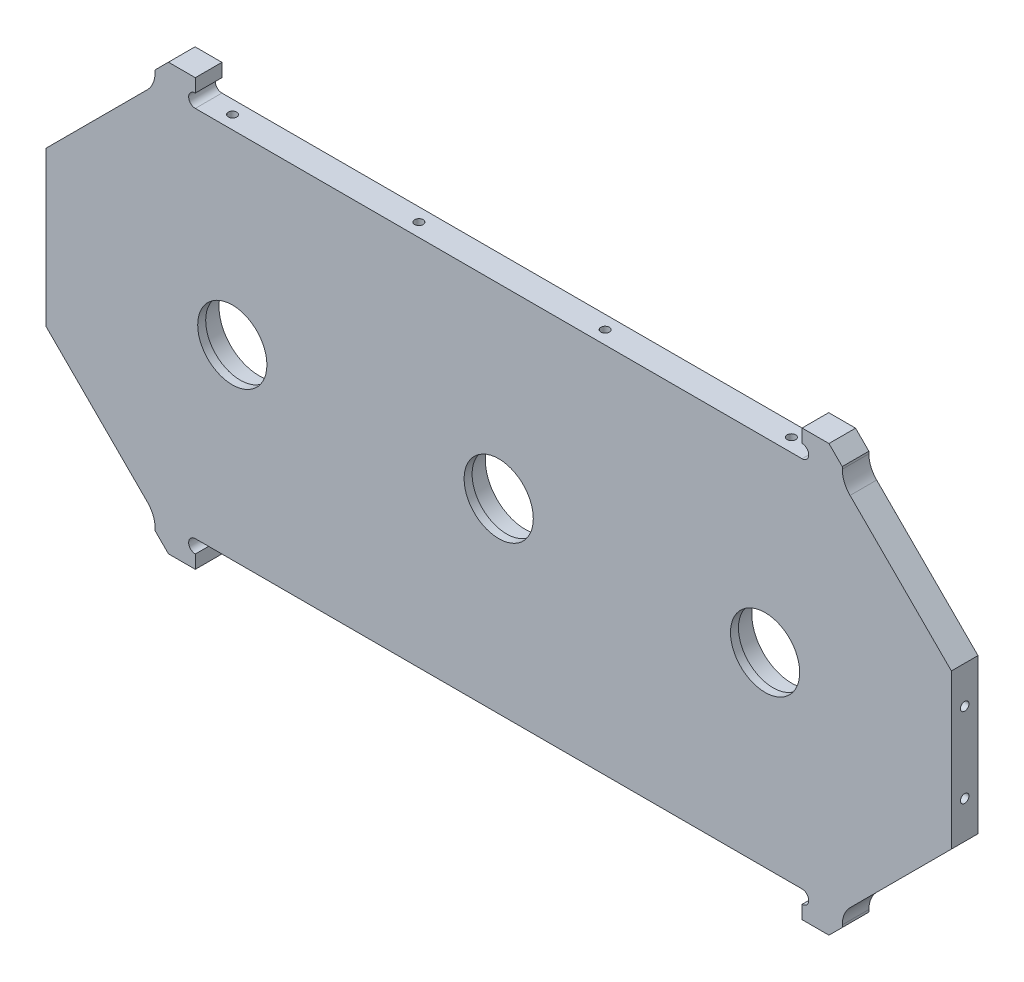
SolidWorks part; units mm, degrees
material "7075-T6，板材(SS)"
ref_plane "前视基准面" through (0, 0, 0) normal (0, 0, 1) x (1, 0, 0)
ref_plane "上视基准面" through (0, 0, 0) normal (0, 1, 0) x (1, 0, 0)
ref_plane "右视基准面" through (0, 0, 0) normal (1, 0, 0) x (0, 0, -1)
sketch "Sketch1" plane through (0, 0, 0) normal (0, 0, 1) x (1, 0, 0)
  line L0 (100.1, 0) -> (-100.1, 0) construction
  line L1 (100.1, -70) -> (-100.1, -70)
  line L2 (100.1, 70) -> (-100.1, 70)
  line L4 (-170.1, -28.9949) -> (-129.0949, -70)
  line L5 (-129.0949, -70) -> (-71.1051, -70)
  line L6 (-71.1051, -70) -> (-30.1, -28.9949)
  line L7 (-30.1, -28.9949) -> (-30.1, 28.9949)
  line L8 (-30.1, 28.9949) -> (-71.1051, 70)
  line L9 (-71.1051, 70) -> (-129.0949, 70)
  line L10 (-129.0949, 70) -> (-170.1, 28.9949)
  line L11 (-170.1, 28.9949) -> (-170.1, -28.9949)
  line L12 (129.0949, 70) -> (71.1051, 70)
  line L13 (71.1051, 70) -> (30.1, 28.9949)
  line L14 (30.1, 28.9949) -> (30.1, -28.9949)
  line L15 (30.1, -28.9949) -> (71.1051, -70)
  line L16 (71.1051, -70) -> (129.0949, -70)
  line L17 (129.0949, -70) -> (170.1, -28.9949)
  line L18 (170.1, -28.9949) -> (170.1, 28.9949)
  line L19 (170.1, 28.9949) -> (129.0949, 70)
  arc A0 (100.1, -70) -> (100.1, 70) centre (100.1, 0) ccw
  arc A1 (-100.1, 70) -> (-100.1, -70) centre (-100.1, 0) ccw
  circle A2 centre (-100.1, 0) radius 13
  circle A3 centre (0, 0) radius 13
  circle A4 centre (100.1, 0) radius 13
  circle A5 centre (-100.1, 0) radius 70 construction
  circle A6 centre (100.1, 0) radius 70 construction
  point P2 (0, 0)
  dimension "D1" = 70
  dimension "D3" = 26
  dimension "D2" = 200.2
extrude "Extrude1" add sketch "Sketch1" along normal blind 10 contours A1 L9 L10 | A1 L10 L11 | A1 L11 L4 | A1 L4 L5 | L2 A1 L1 L6 L7 L8 A2 | L15 L14 L13 L2 L8 L7 L6 L1 A3 | A0 L2 L13 L14 L15 L1 A4 | A0 L16 L17 | A0 L17 L18 | A0 L18 L19 | A0 L19 L12
sketch "Sketch2" plane through (0, 0, 0) normal (0, 0, -1) x (-1, 0, 0)
  circle A0 centre (0, 0) radius 15
  circle A1 centre (-100.1, 0) radius 15
  circle A2 centre (100.1, 0) radius 15
  dimension "D1" = 30
extrude "Extrude2" cut sketch "Sketch2" against normal blind 7
sketch "Sketch3" plane through (0, 0, 0) normal (0, 0, -1) x (-1, 0, 0)
  line L0 (126.6097, 64) -> (-126.6097, 64)
  line L1 (-126.6097, 64) -> (-164.1, 26.5097)
  line L2 (-164.1, 26.5097) -> (-164.1, -26.5097)
  line L3 (-164.1, -26.5097) -> (-126.6097, -64)
  line L4 (-126.6097, -64) -> (126.6097, -64)
  line L5 (126.6097, -64) -> (164.1, -26.5097)
  line L6 (164.1, -26.5097) -> (164.1, 26.5097)
  line L7 (164.1, 26.5097) -> (126.6097, 64)
  line L8 (-129.0949, -70) -> (129.0949, -70)
  line L9 (129.0949, -70) -> (170.1, -28.9949)
  line L10 (170.1, -28.9949) -> (170.1, 28.9949)
  line L11 (170.1, 28.9949) -> (129.0949, 70)
  line L12 (129.0949, 70) -> (-129.0949, 70)
  line L13 (-129.0949, 70) -> (-170.1, 28.9949)
  line L14 (-170.1, 28.9949) -> (-170.1, -28.9949)
  line L15 (-170.1, -28.9949) -> (-129.0949, -70)
  line L16 (-129.0949, -70) -> (129.0949, -70)
  line L17 (129.0949, -70) -> (170.1, -28.9949)
  line L18 (170.1, -28.9949) -> (170.1, 28.9949)
  line L19 (170.1, 28.9949) -> (129.0949, 70)
  line L20 (129.0949, 70) -> (-129.0949, 70)
  line L21 (-129.0949, 70) -> (-170.1, 28.9949)
  line L22 (-170.1, 28.9949) -> (-170.1, -28.9949)
  line L23 (-170.1, -28.9949) -> (-129.0949, -70)
  line L24 (-100.1, 0) -> (-168.983, 166.2983) construction
  line L25 (-101.9478, -0.7654) -> (-170.8308, 165.5329)
  line L26 (-98.2522, 0.7654) -> (-167.1353, 167.0637)
  line L27 (-100.1, 0) -> (-31.217, 166.2983) construction
  line L28 (-101.9478, 0.7654) -> (-33.0647, 167.0637)
  line L29 (-98.2522, -0.7654) -> (-29.3692, 165.5329)
  line L30 (-100.1, 0) -> (66.1983, 68.883) construction
  line L31 (-100.8654, 1.8478) -> (65.4329, 70.7308)
  line L32 (-99.3346, -1.8478) -> (66.9637, 67.0353)
  line L33 (-100.1, 0) -> (66.1983, -68.883) construction
  line L34 (-99.3346, 1.8478) -> (66.9637, -67.0353)
  line L35 (-100.8654, -1.8478) -> (65.4329, -70.7308)
  line L36 (-100.1, 0) -> (-31.217, -166.2983) construction
  line L37 (-98.2522, 0.7654) -> (-29.3692, -165.5329)
  line L38 (-101.9478, -0.7654) -> (-33.0647, -167.0637)
  line L39 (-100.1, 0) -> (-168.983, -166.2983) construction
  line L40 (-98.2522, -0.7654) -> (-167.1353, -167.0637)
  line L41 (-101.9478, 0.7654) -> (-170.8308, -165.5329)
  line L42 (-100.1, 0) -> (-266.3983, -68.883) construction
  line L43 (-99.3346, -1.8478) -> (-265.6329, -70.7308)
  line L44 (-100.8654, 1.8478) -> (-267.1637, -67.0353)
  line L45 (-100.1, 0) -> (-266.3983, 68.883) construction
  line L46 (-100.8654, -1.8478) -> (-267.1637, 67.0353)
  line L47 (-99.3346, 1.8478) -> (-265.6329, 70.7308)
  line L48 (0, 0) -> (0, -70) construction
  line L49 (100.1, 0) -> (168.983, 166.2983) construction
  line L50 (101.9478, -0.7654) -> (170.8308, 165.5329)
  line L51 (98.2522, 0.7654) -> (167.1353, 167.0637)
  line L52 (100.1, 0) -> (31.217, 166.2983) construction
  line L53 (101.9478, 0.7654) -> (33.0647, 167.0637)
  line L54 (98.2522, -0.7654) -> (29.3692, 165.5329)
  line L55 (100.1, 0) -> (-66.1983, 68.883) construction
  line L56 (100.8654, 1.8478) -> (-65.4329, 70.7308)
  line L57 (99.3346, -1.8478) -> (-66.9637, 67.0353)
  line L58 (100.1, 0) -> (-66.1983, -68.883) construction
  line L59 (99.3346, 1.8478) -> (-66.9637, -67.0353)
  line L60 (100.8654, -1.8478) -> (-65.4329, -70.7308)
  line L61 (100.1, 0) -> (31.217, -166.2983) construction
  line L62 (98.2522, 0.7654) -> (29.3692, -165.5329)
  line L63 (101.9478, -0.7654) -> (33.0647, -167.0637)
  line L64 (100.1, 0) -> (168.983, -166.2983) construction
  line L65 (98.2522, -0.7654) -> (167.1353, -167.0637)
  line L66 (101.9478, 0.7654) -> (170.8308, -165.5329)
  line L67 (100.1, 0) -> (266.3983, -68.883) construction
  line L68 (99.3346, -1.8478) -> (265.6329, -70.7308)
  line L69 (100.8654, 1.8478) -> (267.1637, -67.0353)
  line L70 (100.1, 0) -> (266.3983, 68.883) construction
  line L71 (100.8654, -1.8478) -> (267.1637, 67.0353)
  line L72 (99.3346, 1.8478) -> (265.6329, 70.7308)
  line L73 (170.1, -28.9949) -> (129.0949, -70)
  line L74 (170.1, 28.9949) -> (170.1, -28.9949)
  line L75 (129.0949, 70) -> (170.1, 28.9949)
  line L76 (-129.0949, 70) -> (129.0949, 70)
  line L77 (-170.1, 28.9949) -> (-129.0949, 70)
  line L78 (-170.1, -28.9949) -> (-170.1, 28.9949)
  line L79 (-129.0949, -70) -> (-170.1, -28.9949)
  line L80 (129.0949, -70) -> (-129.0949, -70)
  line L81 (-164.1, 26.5097) -> (-126.6097, 64)
  line L82 (-164.1, -26.5097) -> (-164.1, 26.5097)
  line L83 (-126.6097, -64) -> (-164.1, -26.5097)
  line L84 (126.6097, -64) -> (-126.6097, -64)
  line L85 (164.1, -26.5097) -> (126.6097, -64)
  line L86 (164.1, 26.5097) -> (164.1, -26.5097)
  line L87 (126.6097, 64) -> (164.1, 26.5097)
  line L88 (-126.6097, 64) -> (126.6097, 64)
  line L89 (0, 70) -> (0, -70) construction
  line L90 (2, 70) -> (2, -70)
  line L91 (-2, 70) -> (-2, -70)
  line L92 (-100.1, 0) -> (100.1, 0) construction
  line L93 (-100.1, 2) -> (100.1, 2)
  line L94 (-100.1, -2) -> (100.1, -2)
  arc A0 (-101.9478, -0.7654) -> (-98.2522, 0.7654) centre (-100.1, 0) ccw
  arc A1 (-167.1353, 167.0637) -> (-170.8308, 165.5329) centre (-168.983, 166.2983) ccw
  arc A2 (-101.9478, 0.7654) -> (-98.2522, -0.7654) centre (-100.1, 0) ccw
  arc A3 (-29.3692, 165.5329) -> (-33.0647, 167.0637) centre (-31.217, 166.2983) ccw
  arc A4 (-100.8654, 1.8478) -> (-99.3346, -1.8478) centre (-100.1, 0) ccw
  arc A5 (66.9637, 67.0353) -> (65.4329, 70.7308) centre (66.1983, 68.883) ccw
  arc A6 (-99.3346, 1.8478) -> (-100.8654, -1.8478) centre (-100.1, 0) ccw
  arc A7 (65.4329, -70.7308) -> (66.9637, -67.0353) centre (66.1983, -68.883) ccw
  arc A8 (-98.2522, 0.7654) -> (-101.9478, -0.7654) centre (-100.1, 0) ccw
  arc A9 (-33.0647, -167.0637) -> (-29.3692, -165.5329) centre (-31.217, -166.2983) ccw
  arc A10 (-98.2522, -0.7654) -> (-101.9478, 0.7654) centre (-100.1, 0) ccw
  arc A11 (-170.8308, -165.5329) -> (-167.1353, -167.0637) centre (-168.983, -166.2983) ccw
  arc A12 (-99.3346, -1.8478) -> (-100.8654, 1.8478) centre (-100.1, 0) ccw
  arc A13 (-267.1637, -67.0353) -> (-265.6329, -70.7308) centre (-266.3983, -68.883) ccw
  arc A14 (-100.8654, -1.8478) -> (-99.3346, 1.8478) centre (-100.1, 0) ccw
  arc A15 (-265.6329, 70.7308) -> (-267.1637, 67.0353) centre (-266.3983, 68.883) ccw
  arc A16 (101.9478, -0.7654) -> (98.2522, 0.7654) centre (100.1, 0) cw
  arc A17 (167.1353, 167.0637) -> (170.8308, 165.5329) centre (168.983, 166.2983) cw
  arc A18 (101.9478, 0.7654) -> (98.2522, -0.7654) centre (100.1, 0) cw
  arc A19 (29.3692, 165.5329) -> (33.0647, 167.0637) centre (31.217, 166.2983) cw
  arc A20 (100.8654, 1.8478) -> (99.3346, -1.8478) centre (100.1, 0) cw
  arc A21 (-66.9637, 67.0353) -> (-65.4329, 70.7308) centre (-66.1983, 68.883) cw
  arc A22 (99.3346, 1.8478) -> (100.8654, -1.8478) centre (100.1, 0) cw
  arc A23 (-65.4329, -70.7308) -> (-66.9637, -67.0353) centre (-66.1983, -68.883) cw
  arc A24 (98.2522, 0.7654) -> (101.9478, -0.7654) centre (100.1, 0) cw
  arc A25 (33.0647, -167.0637) -> (29.3692, -165.5329) centre (31.217, -166.2983) cw
  arc A26 (98.2522, -0.7654) -> (101.9478, 0.7654) centre (100.1, 0) cw
  arc A27 (170.8308, -165.5329) -> (167.1353, -167.0637) centre (168.983, -166.2983) cw
  arc A28 (99.3346, -1.8478) -> (100.8654, 1.8478) centre (100.1, 0) cw
  arc A29 (267.1637, -67.0353) -> (265.6329, -70.7308) centre (266.3983, -68.883) cw
  arc A30 (100.8654, -1.8478) -> (99.3346, 1.8478) centre (100.1, 0) cw
  arc A31 (265.6329, 70.7308) -> (267.1637, 67.0353) centre (266.3983, 68.883) cw
  circle A34 centre (-100.1, 0) radius 19
  circle A35 centre (-100.1, 0) radius 19
  circle A37 centre (0, 0) radius 19
  circle A38 centre (0, 0) radius 19
  arc A39 (2, 70) -> (-2, 70) centre (0, 70) ccw
  circle A40 centre (100.1, 0) radius 19
  circle A41 centre (100.1, 0) radius 19
  arc A42 (-2, -70) -> (2, -70) centre (0, -70) ccw
  arc A43 (-100.1, 2) -> (-100.1, -2) centre (-100.1, 0) ccw
  arc A44 (100.1, -2) -> (100.1, 2) centre (100.1, 0) ccw
  point P19 (-134.5415, 83.1492)
  point P28 (-65.6585, 83.1492)
  point P35 (-16.9508, 34.4415)
  point P42 (-16.9508, -34.4415)
  point P49 (-65.6585, -83.1492)
  point P56 (-134.5415, -83.1492)
  point P63 (-183.2492, -34.4415)
  point P70 (-183.2492, 34.4415)
  point P78 (134.5415, 83.1492)
  point P85 (65.6585, 83.1492)
  point P92 (16.9508, 34.4415)
  point P99 (16.9508, -34.4415)
  point P106 (65.6585, -83.1492)
  point P113 (134.5415, -83.1492)
  point P120 (183.2492, -34.4415)
  point P127 (183.2492, 34.4415)
  point P133 (0, 0)
  point P148 (0, 0)
  dimension "D3" = 4
  dimension "D5" = 180
  dimension "D9" = 4
  dimension "D10" = 4
  dimension "D1" = 0
  dimension "D2" = 6
  dimension "D6" = 4
  dimension "D7" = 4
  dimension "D8" = 4
  dimension "D4" = 8
extrude "Extrude3" cut sketch "Sketch3" against normal blind 8 contours A35 L25 L1 L47 | A35 L46 L2 L44 | A35 L43 L3 L41 | A35 L40 L4 L38 | A35 L37 L4 L59 L35 | A38 L94 A35 L34 L91 | A38 L91 L32 A35 L93 | A35 L31 L57 L0 L29 | A35 L28 L0 L26 | L91 L0 L56 | L88 L91 L56 L31 L90 | L0 L90 L31 | L91 L60 L4 | L35 L90 L84 | L60 L91 L84 L90 L35 | A41 L60 L34 L4 L62 | A41 L94 A38 L90 L59 | A41 L57 L90 A38 L93 | A41 L54 L0 L32 L56 | A41 L51 L0 L53 | A41 L72 L7 L50 | A41 L69 L6 L71 | A41 L66 L5 L68 | A41 L63 L4 L65
fillet "Fillet2" radius 2 86 edges at (-83.4092, -9.0783, 4) (-5.2263, -41.4628, 4) (-59.6359, -64, 4) (-71.4255, -64, 4) (-91.0217, -16.6908, 4) (0, 43.6276, 4) (-49.1834, 64, 4) (49.1834, 64, 4) (-116.7908, 9.0783, 4) (-162.5693, 28.0404, 4) (-128.1404, 62.4693, 4) (-109.1783, 16.6908, 4) (-91.0217, 16.6908, 4) (-71.4255, 64, 4) (-59.6359, 64, 4) (-5.2263, 41.4628, 4) (-83.4092, 9.0783, 4) (91.0217, -16.6908, 4) (71.4255, -64, 4) (59.6359, -64, 4) (5.2263, -41.4628, 4) (83.4092, -9.0783, 4) (116.7908, -9.0783, 4) (162.5693, -28.0404, 4) (128.1404, -62.4693, 4) (109.1783, -16.6908, 4) (94.7172, 18.2216, 4) (75.7551, 64, 4) (124.4449, 64, 4) (105.4828, 18.2216, 4) (18.8944, -2, 4) (81.2056, -2, 4) (81.8784, -5.3828, 4) (2, -38.4696, 4) (2, -18.8944, 4) (-118.3216, -5.3828, 4) (-164.1, -24.3449, 4) (-164.1, 24.3449, 4) (-118.3216, 5.3828, 4) (109.1783, 16.6908, 4) (128.1404, 62.4693, 4) (162.5693, 28.0404, 4) (116.7908, 9.0783, 4) (-109.1783, -16.6908, 4) (-128.1404, -62.4693, 4) (-162.5693, -28.0404, 4) (-116.7908, -9.0783, 4) (-94.7172, -18.2216, 4) (-75.7551, -64, 4) (-124.4449, -64, 4) (-105.4828, -18.2216, 4) (2, 18.8944, 4) (2, 38.4696, 4) (81.8784, 5.3828, 4) (81.2056, 2, 4) (83.4092, 9.0783, 4) (5.2263, 41.4628, 4) (59.6359, 64, 4) (71.4255, 64, 4) (91.0217, 16.6908, 4) (118.3216, 5.3828, 4) (164.1, 24.3449, 4) (164.1, -24.3449, 4) (118.3216, -5.3828, 4) (105.4828, -18.2216, 4) (124.4449, -64, 4) (75.7551, -64, 4) (94.7172, -18.2216, 4) (-81.8784, 5.3828, 4) (-2, 38.4696, 4) (-2, 18.8944, 4) (-18.8944, 2, 4) (-81.2056, 2, 4) (-105.4828, 18.2216, 4) (-124.4449, 64, 4) (-75.7551, 64, 4) (-94.7172, 18.2216, 4) (0, -43.6276, 4) (49.1834, -64, 4) (-49.1834, -64, 4) (-81.2056, -2, 4) (-18.8944, -2, 4) (-2, -18.8944, 4) (-2, -38.4696, 4) (-81.8784, -5.3828, 4) (18.8944, 2, 4)
sketch "Sketch4" plane through (0, 70, 0) normal (0, 1, 0) x (1, 0, 0)
  line L0 (0, 0) -> (0, -10) construction
  line L1 (129.0949, -10) -> (-129.0949, -10) construction
  line L2 (105, -5) -> (35, -5) construction
  line L3 (35, -5) -> (-35, -5) construction
  circle A0 centre (35, -5) radius 1.6
  circle A1 centre (105, -5) radius 1.6
  circle A2 centre (-105, -5) radius 1.6
  circle A3 centre (-35, -5) radius 1.6
  point P7 (0, -5)
  dimension "D1" = 3.2
  dimension "D2" = 70
extrude "Extrude4" cut sketch "Sketch4" against normal blind 6
cosmetic thread "Cosmetic Thread1" parameters "D2"=4
cosmetic thread "Cosmetic Thread2" parameters "D2"=4
cosmetic thread "Cosmetic Thread3" parameters "D2"=4
cosmetic thread "Cosmetic Thread4" parameters "D2"=4
sketch "Sketch5" plane through (0, 0, 0) normal (0, 0, -1) x (-1, 0, 0)
  line L0 (0, 70) -> (0, 0) construction
  line L1 (-129.0949, 70) -> (-114, 70)
  line L2 (-129.0949, 70) -> (-129.0949, 80)
  line L3 (-129.0949, 80) -> (-114, 80)
  line L4 (-114, 70) -> (-114, 80)
  line L5 (-129.0949, 70) -> (129.0949, 70) construction
  line L6 (0, 0) -> (-100.1, 0) construction
  dimension "D1" = 10
  dimension "D2" = 114
extrude "Extrude5" add sketch "Sketch5" against normal up to surface (10 mm away) up to face at (0, 0, 10)
sketch "Sketch6" plane through (0, 0, 0) normal (0, 0, -1) x (-1, 0, 0)
  line L0 (-114, 70) -> (-114, 80) construction
  circle A0 centre (-114, 72.5) radius 2.5
  dimension "D1" = 5
extrude "Extrude6" cut sketch "Sketch6" against normal through all
mirror "Mirror1" about plane through (0, 0, 0) normal (0, 1, 0) of "Extrude6", "Extrude5"
mirror "Mirror2" about plane through (0, 0, 0) normal (1, 0, 0) of "Mirror1", "Extrude5", "Extrude6"
mirror "Mirror3" about plane through (0, 0, 0) normal (0, 1, 0) of "Extrude4"
cosmetic thread "装饰螺纹线1" parameters "D2"=4
cosmetic thread "装饰螺纹线2" parameters "D2"=4
cosmetic thread "装饰螺纹线3" parameters "D2"=4
cosmetic thread "装饰螺纹线4" parameters "D2"=4
fillet "Fillet3" radius 10 4 edges at (-129.0949, 70, 5) (-129.0949, -70, 5) (129.0949, -70, 5) (129.0949, 70, 5)
chamfer "Chamfer1" distance 5 angle 45 4 edges at (-129.0949, -80, 5) (129.0949, -80, 5) (-129.0949, 80, 5) (129.0949, 80, 5)
sketch "Sketch7" plane through (170.1, 0, 0) normal (1, 0, 0) x (0, 0, -1)
  line L0 (0, 0) -> (-10, 0) construction
  line L1 (-10, -28.9949) -> (-10, 28.9949) construction
  circle A0 centre (-5, 15) radius 1.6
  circle A1 centre (-5, -15) radius 1.6
  point P9 (0, 0)
  point P10 (-5, 0)
  dimension "D1" = 3.2
  dimension "D2" = 30
extrude "Extrude7" cut sketch "Sketch7" against normal up to next
cosmetic thread "Cosmetic Thread5" parameters "D2"=4
cosmetic thread "Cosmetic Thread6" parameters "D2"=4
mirror "Mirror4" about plane through (0, 0, 0) normal (1, 0, 0) of "Extrude7"
cosmetic thread "装饰螺纹线5" parameters "D2"=4
cosmetic thread "装饰螺纹线6" parameters "D2"=4
